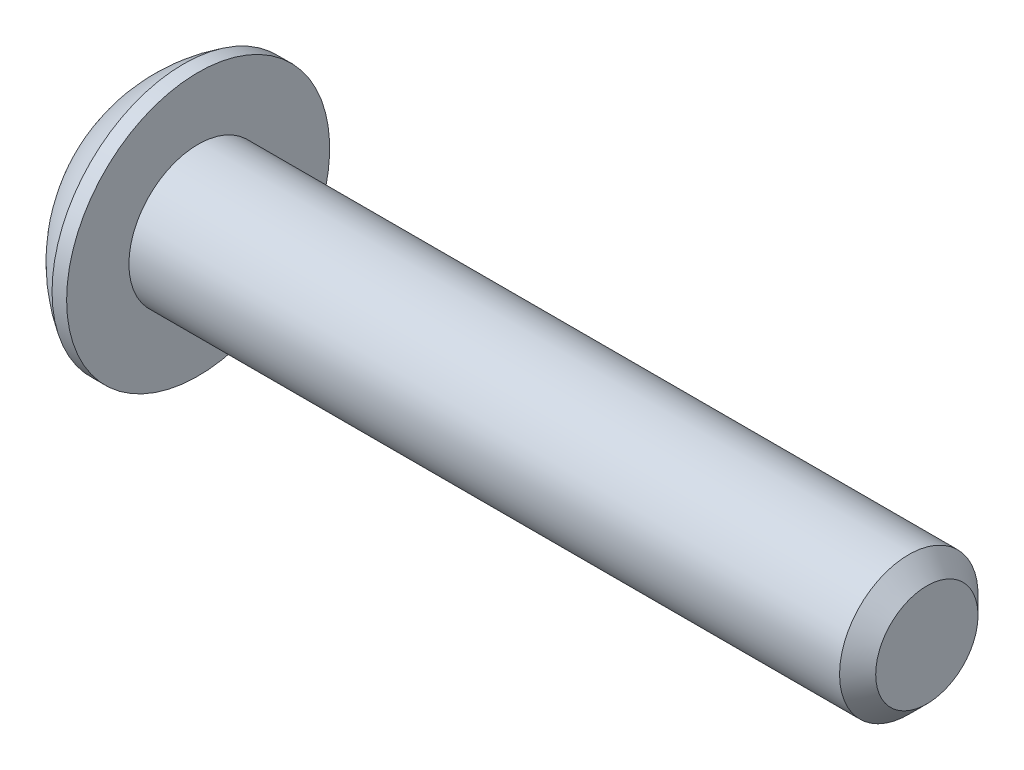
SolidWorks part; units mm, degrees
ref_plane "Plane1" through (0, 0, 0) normal (0, 0, 1) x (1, 0, 0)
ref_plane "Plane2" through (0, 0, 0) normal (0, 1, 0) x (1, 0, 0)
ref_plane "Plane3" through (0, 0, 0) normal (1, 0, 0) x (0, 0, -1)
sketch "BodySke" plane through (0, 0, 0) normal (0, 0, 1) x (1, 0, 0)
  line L0 (27.9654, 0) -> (27.9654, 1.7831)
  line L1 (27.3355, 2.413) -> (2.5654, 2.413)
  line L2 (2.5654, 2.413) -> (2.5654, 4.5847)
  line L3 (2.5654, 4.5847) -> (2.0574, 4.5847)
  line L4 (0, 0) -> (101.6, 0) construction
  line L5 (2.5654, -4.5847) -> (2.0574, -4.5847) construction
  line L6 (55.6768, -2.413) -> (2.5654, -2.413) construction
  line L7 (27.9654, 0) -> (0, 0)
  line L8 (0, 2.2923) -> (0, -2.2923) construction
  line L9 (0, 0) -> (0, 2.2923)
  line L10 (27.9654, 1.7831) -> (27.3355, 2.413)
  line L11 (27.9654, -1.7831) -> (27.3355, -2.413) construction
  line L12 (3.6246, 9.525) -> (3.6246, -2.413) construction
  line L13 (2.5654, 9.525) -> (2.5654, -2.413) construction
  arc A1 (0, 2.2923) -> (2.0574, 4.5847) centre (4.8599, 0) cw
  dimension "D1" = 4.5847
  dimension "Diameter" = 4.826
  dimension "Length" = 25.4
  dimension "Head_dia" = 9.1694
  dimension "Head_ht" = 2.5654
  dimension "Head_side_ht" = 0.508
  dimension "Minor_dia" = 3.5662
  dimension "Body_ch_ang" = 45
  dimension "Advance" = 1.0592
  dimension "Thread_nom" = 25.4
revolve "BaseBody" add sketch "BodySke" angle 360 about L4
cosmetic thread "ThreadCosmetic" [suppressed] parameters "Thread_length"=24.3408, "Thread_minor"=3.5662
sketch "Sketch2" plane through (0, 0, 0) normal (0, 0, 1) x (1, 0, 0)
  line L0 (0, 1.5875) -> (1.778, 1.5875)
  line L1 (1.778, 1.5875) -> (2.6945, 0)
  line L3 (2.6945, 0) -> (0, 0)
  line L4 (0, 0) -> (0, 1.5875)
  line L5 (0, -1.5875) -> (1.778, -1.5875) construction
  line L6 (0, 0) -> (47.625, 0) construction
  dimension "D2" = 60
  dimension "PreBroach_depth" = 1.778
  dimension "PreBroach_dia" = 3.175
revolve "PreBroach" cut sketch "Sketch2" angle 360 about L6
sketch "Sketch3" plane through (0, 0, 0) normal (1, 0, 0) x (0, 0, -1)
  line L0 (-1.5875, -0.9165) -> (-1.5875, 0.9165)
  line L1 (-1.5875, 0.9165) -> (0, 1.8331)
  line L2 (0, 1.8331) -> (1.5875, 0.9165)
  line L3 (1.5875, 0.9165) -> (1.5875, -0.9165)
  line L4 (1.5875, -0.9165) -> (0, -1.8331)
  line L5 (0, -1.8331) -> (-1.5875, -0.9165)
  dimension "D1" = 1.5875
  dimension "D2" = 1.5875
  dimension "D3" = 3.175
  dimension "Hex_size" = 3.175
extrude "Hex" cut sketch "Sketch3" along normal blind 1.778
sketch "Sketch4" plane through (0, 9.525, 0) normal (1, 0, 0) x (0, 0, -1)
  line L0 (0, -9.525) -> (1.8923, -9.525)
  line L1 (0, -9.525) -> (6.1484, -5.9752) construction
  line L2 (0, -9.525) -> (0.9461, -7.8862)
  line L3 (1.5663, -9.09) -> (1.8037, -8.9529)
  line L4 (1.1599, -8.3861) -> (1.3973, -8.249)
  arc A0 (1.5663, -9.09) -> (1.1599, -8.3861) centre (0, -9.525) ccw
  arc A1 (1.8923, -9.525) -> (1.8037, -8.9529) centre (0, -9.525) ccw
  arc A2 (0.9461, -7.8862) -> (1.3973, -8.249) centre (0, -9.525) cw
  dimension "D1" = 30
  dimension "Spline_n_dim" = 3.2512
  dimension "Spline_m_dim" = 3.7846
  dimension "D2" = 60
  dimension "D3" = 0.4064
  dimension "Spline_p_dim" = 0.8128
extrude "Spline" [suppressed] cut sketch "Sketch4" along normal blind 1.778
pattern_circular "CirPattern1" [suppressed] count 6 every 60 about axis through (0, 0, 0) along (1, 0, 0)
sketch "ThdSchSke" plane through (0, 0, 0) normal (0, 0, 1) x (1, 0, 0)
  line L0 (3.6246, -1.7831) -> (3.1835, -2.413)
  line L1 (3.6246, -1.7831) -> (4.0657, -2.413)
  line L2 (4.0657, -2.413) -> (4.0657, -3.0162)
  line L3 (-3.175, 0) -> (5.1513, 0) construction
  line L5 (4.0657, -3.0162) -> (3.1835, -3.0162)
  line L6 (3.1835, -3.0162) -> (3.1835, -2.413)
  dimension "Thread_minor" = 3.5662
  dimension "Diameter" = 4.826
  dimension "Start" = 3.6246
  dimension "SideAngle" = 55
  dimension "VeeAngle" = 70
  dimension "Overcut" = 6.0325
revolve "ThreadSchematic" [suppressed] cut sketch "ThdSchSke" angle 360 about L3
pattern_linear "ThdSchPat" [suppressed]
equation "\"D1@BodySke\" = \"Head_dia@BodySke\" * .5"
equation "\"Thread_minor@ThreadCosmetic\" = \"Minor_dia@BodySke\""
equation "\"D1@Sketch3\" = \"Hex_size@Sketch3\" / 2"
equation "\"D2@Sketch3\" = \"D1@Sketch3\""
equation "\"D3@Sketch3\" = \"Hex_size@Sketch3\""
equation "\"D3@Sketch4\" = \"Spline_p_dim@Sketch4\" / 2"
equation "\"D1@Sketch4\" = \"D2@Sketch4\" / 2"
equation "\"Thread_length@ThreadCosmetic\" = ((sgn( (\"Length@BodySke\" - \"Advance@BodySke\" ) - \"Thread_nom@BodySke\" )-1)*( (\"Length@BodySke\" - \"Advance@BodySke\" ) - \"Thread_nom@BodySke\" ))/-2+ \"Thread_nom@BodySke\""
equation "\"Thread_minor@ThdSchSke\" = \"Minor_dia@BodySke\""
equation "\"Diameter@ThdSchSke\" = \"Diameter@BodySke\""
equation "\"Overcut@ThdSchSke\" = \"Diameter@BodySke\" * 1.25"
equation "\"Start@ThdSchSke\" = \"Head_ht@BodySke\" + \"Length@BodySke\" - \"Thread_length@ThreadCosmetic\"  '---Non-countersunk---"
equation "\"Num_threads@ThdSchPat\" = int( \"Thread_length@ThreadCosmetic\" / \"Advance@BodySke\" + 0.999 )  + 1"
equation "\"Advance@ThdSchPat\" = \"Thread_length@ThreadCosmetic\" /  (\"Num_threads@ThdSchPat\" - 1) 'relax it"
equation "\"Num_threads@ThdSchPat\" = \"Num_threads@ThdSchPat\" - sgn( \"Num_threads@ThdSchPat\" - 1) '---chamfered tips only---"
